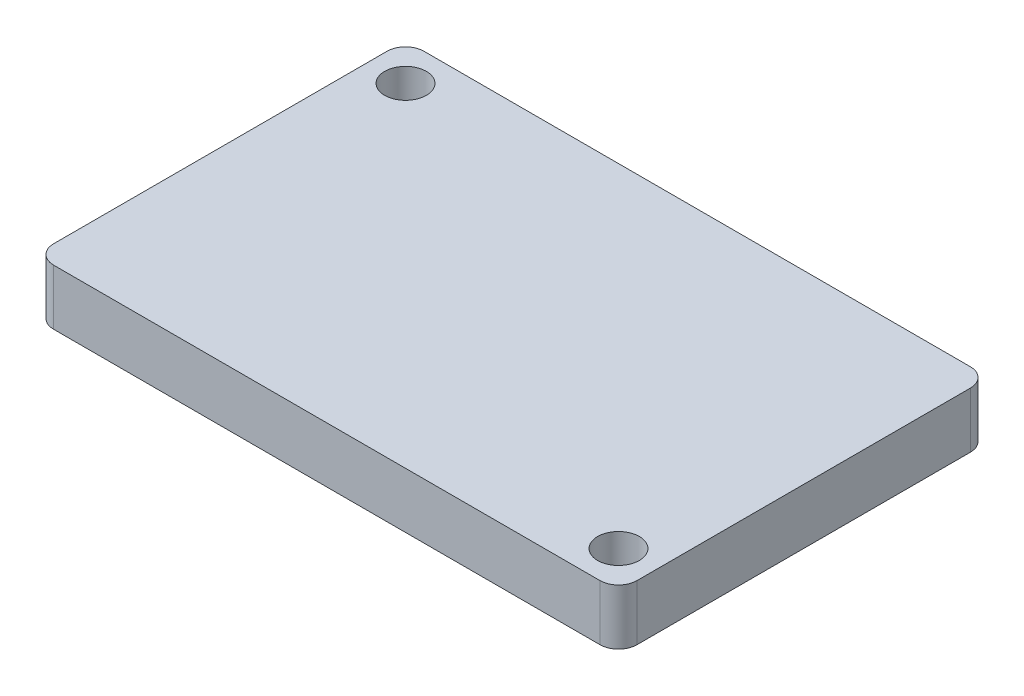
SolidWorks part; units mm, degrees
ref_plane "前视基准面" through (0, 0, 0) normal (0, 0, 1) x (1, 0, 0)
ref_plane "上视基准面" through (0, 0, 0) normal (0, 1, 0) x (1, 0, 0)
ref_plane "右视基准面" through (0, 0, 0) normal (1, 0, 0) x (0, 0, -1)
other "Configuration Table"
sketch "草图1" plane through (0, 0, 0) normal (0, 0, 1) x (1, 0, 0)
  line L0 (0, 0) -> (63, 0)
  line L1 (63, 0) -> (63, 6)
  line L2 (63, 6) -> (0, 6)
  line L3 (0, 6) -> (0, 0)
  dimension "width" = 63
  dimension "height" = 6
extrude "BlockExtrude" add sketch "草图1" along normal blind 40
fillet "Fillet" radius 2 4 edges at (0, 3, 0) (63, 3, 0) (0, 3, 40) (63, 3, 40)
sketch "草图2" plane through (0, 6, 0) normal (0, 1, 0) x (1, 0, 0)
  circle A0 centre (4, -4) radius 2.25
  dimension "diameter" = 4.5
  dimension "x" = 4
  dimension "y" = 4
extrude "Mounting_hole" cut sketch "草图2" against normal through all
sketch "草图3" plane through (0, 6, 0) normal (0, 1, 0) x (1, 0, 0)
  circle A0 centre (59, -36) radius 2.25
  dimension "diameter" = 4.5
  dimension "x" = 59
  dimension "y" = 36
extrude "切除-拉伸2" cut sketch "草图3" against normal through all
